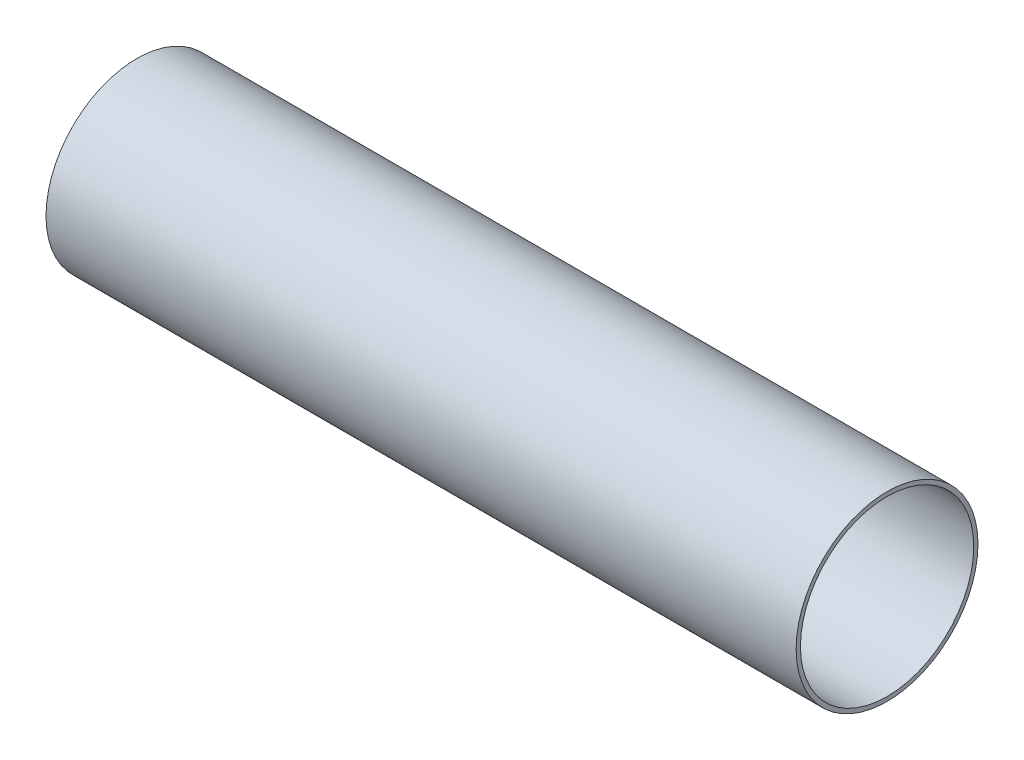
SolidWorks part; units mm, degrees
material "6061-T6 (SS)"
ref_plane "Front Plane" through (0, 0, 0) normal (0, 0, 1) x (1, 0, 0)
ref_plane "Top Plane" through (0, 0, 0) normal (0, 1, 0) x (1, 0, 0)
ref_plane "Right Plane" through (0, 0, 0) normal (1, 0, 0) x (0, 0, -1)
sketch "Sketch1" plane through (0, 0, 0) normal (1, 0, 0) x (0, 0, -1)
  circle A0 centre (0, 0) radius 101.6
  circle A1 centre (0, 0) radius 96.8375
  dimension "D1" = 203.2
  dimension "D2" = 4.7625
extrude "Boss-Extrude1" add sketch "Sketch1" along normal blind 838.2
